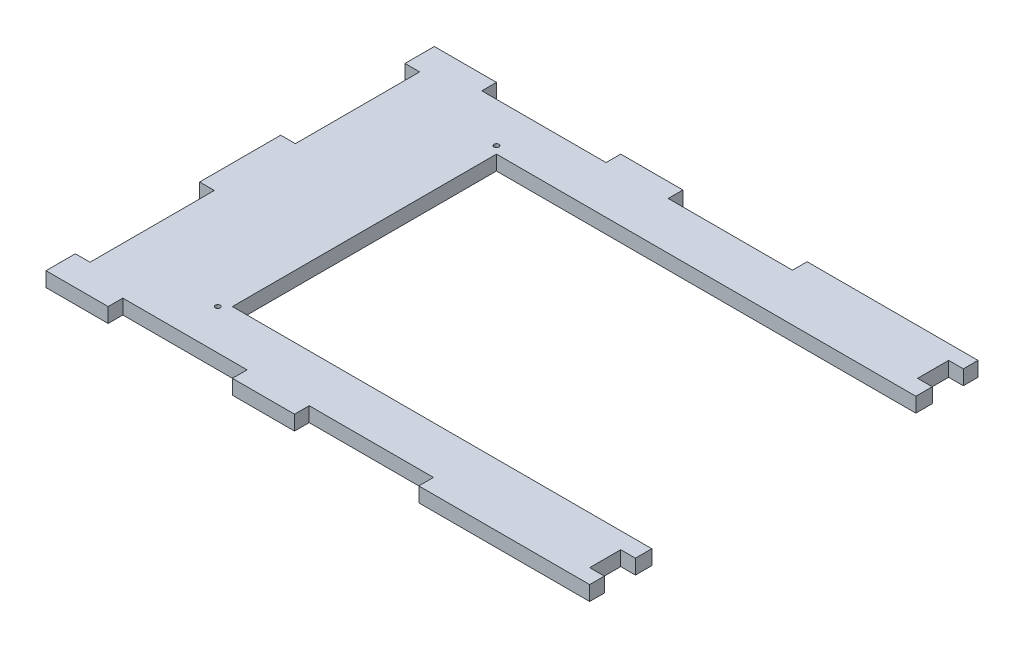
SolidWorks part; units mm, degrees
ref_plane "Front Plane" through (0, 0, 0) normal (0, 0, 1) x (1, 0, 0)
ref_plane "Top Plane" through (0, 0, 0) normal (0, 1, 0) x (1, 0, 0)
ref_plane "Right Plane" through (0, 0, 0) normal (1, 0, 0) x (0, 0, -1)
sketch "Sketch1" plane through (0, 0, 0) normal (0, 1, 0) x (1, 0, 0)
  line L0 (42.8625, 26.9875) -> (42.8625, 30.3375)
  line L1 (-42.8625, -26.9875) -> (42.8625, -26.9875)
  line L2 (-42.8625, -26.9875) -> (-42.8625, 26.9875)
  line L3 (-42.8625, 26.9875) -> (42.8625, 26.9875)
  line L4 (-42.8625, 26.9875) -> (-44.3616, 28.4866) construction
  line L5 (-42.8625, -26.9875) -> (42.8625, 26.9875) construction
  line L6 (-42.8625, 26.9875) -> (42.8625, -26.9875) construction
  line L7 (42.8625, -39.6875) -> (7.9375, -39.6875)
  line L8 (-42.8625, -26.9875) -> (-44.3616, -28.4866) construction
  line L9 (42.8625, 39.6875) -> (7.9375, 39.6875)
  line L10 (-68.2625, -39.6875) -> (-68.2625, -33.6875)
  line L11 (42.8625, -26.9875) -> (42.8625, -30.3375)
  line L12 (42.8625, -30.3375) -> (39.8625, -30.3375)
  line L13 (39.8625, -30.3375) -> (39.8625, -36.6875)
  line L14 (39.8625, -36.6875) -> (42.8625, -36.6875)
  line L15 (42.8625, 36.6875) -> (39.8625, 36.6875)
  line L16 (39.8625, 36.6875) -> (39.8625, 30.3375)
  line L17 (39.8625, 30.3375) -> (42.8625, 30.3375)
  line L18 (42.8625, 36.6875) -> (42.8625, 39.6875)
  line L19 (42.8625, -36.6875) -> (42.8625, -39.6875)
  line L20 (-55.5625, -39.6875) -> (-55.5625, -36.6875)
  line L21 (-55.5625, -36.6875) -> (-30.1625, -36.6875)
  line L22 (-30.1625, -36.6875) -> (-30.1625, -39.6875)
  line L23 (-55.5625, -39.6875) -> (-68.2625, -39.6875)
  line L24 (-17.4625, -36.6875) -> (7.9375, -36.6875)
  line L25 (-17.4625, -39.6875) -> (-17.4625, -36.6875)
  line L26 (7.9375, -36.6875) -> (7.9375, -39.6875)
  line L27 (-17.4625, -39.6875) -> (-30.1625, -39.6875)
  line L28 (-55.5625, 39.6875) -> (-55.5625, 36.6875)
  line L29 (-55.5625, 36.6875) -> (-30.1625, 36.6875)
  line L30 (-30.1625, 36.6875) -> (-30.1625, 39.6875)
  line L31 (-55.5625, 39.6875) -> (-68.2625, 39.6875)
  line L32 (-17.4625, 39.6875) -> (-17.4625, 36.6875)
  line L33 (-17.4625, 36.6875) -> (7.9375, 36.6875)
  line L34 (7.9375, 36.6875) -> (7.9375, 39.6875)
  line L35 (-17.4625, 39.6875) -> (-30.1625, 39.6875)
  line L36 (-68.2625, -33.6875) -> (-65.2625, -33.6875)
  line L37 (-65.2625, -33.6875) -> (-65.2625, -8.2875)
  line L38 (-65.2625, -8.2875) -> (-68.2625, -8.2875)
  line L39 (-68.2625, 8.2875) -> (-65.2625, 8.2875)
  line L40 (-65.2625, 8.2875) -> (-65.2625, 33.6875)
  line L41 (-65.2625, 33.6875) -> (-68.2625, 33.6875)
  line L42 (-68.2625, -8.2875) -> (-68.2625, 8.2875)
  line L43 (-68.2625, 33.6875) -> (-68.2625, 39.6875)
  circle A0 centre (-44.3616, 28.4866) radius 0.5
  circle A1 centre (-44.3616, -28.4866) radius 0.5
  point P0 (0, 0)
  point P6 (0, 0)
  dimension "D7" = 1
  dimension "D9" = 1
  dimension "D1" = 85.725
  dimension "D2" = 53.975
  dimension "D3" = 25.4
  dimension "D4" = 12.7
  dimension "D5" = 12.7
  dimension "D6" = 2.12
  dimension "D8" = 2.12
  dimension "D10" = 3
  dimension "D11" = 6.35
  dimension "D12" = 3
  dimension "D13" = 3
  dimension "D14" = 6.35
  dimension "D15" = 3
  dimension "D16" = 12.7
  dimension "D17" = 25.4
  dimension "D18" = 3
  dimension "D20" = 3
  dimension "D21" = 3
  dimension "D22" = 25.4
  dimension "D23" = 6
  dimension "D24" = 3
  dimension "D25" = 25.4
  dimension "D26" = 6
  dimension "D19" = 2
extrude "Boss-Extrude1" add sketch "Sketch1" along normal blind 3
